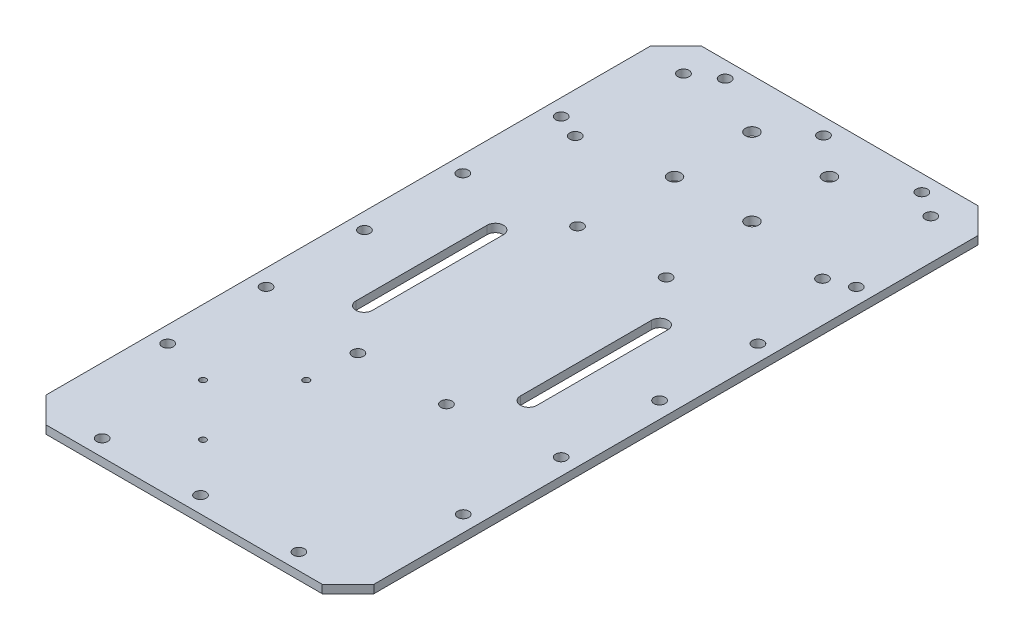
SolidWorks part; units mm, degrees
ref_plane "Front Plane" through (0, 0, 0) normal (0, 0, 1) x (1, 0, 0)
ref_plane "Top Plane" through (0, 0, 0) normal (0, 1, 0) x (1, 0, 0)
ref_plane "Right Plane" through (0, 0, 0) normal (1, 0, 0) x (0, 0, -1)
sketch "Sketch2" plane through (0, 0, 0) normal (0, 1, 0) x (1, 0, 0)
  line L0 (0, 10) -> (0, 244)
  line L1 (10, 254) -> (117, 254)
  line L2 (127, 244) -> (127, 10)
  line L3 (117, 0) -> (10, 0)
  line L4 (0, 244) -> (10, 254)
  line L5 (117, 254) -> (127, 244)
  line L6 (127, 10) -> (117, 0)
  line L7 (10, 0) -> (0, 10)
  line L8 (63.5, 254) -> (63.5, 243.84) construction
  line L9 (15.621, 241.3) -> (15.621, 199.39) construction
  line L10 (0, 127) -> (127, 127) construction
  line L11 (63.5, 243.84) -> (63.5, 199.39) construction
  line L12 (15.621, 199.39) -> (111.379, 199.39) construction
  line L13 (111.379, 199.39) -> (111.379, 241.3) construction
  line L14 (111.379, 241.3) -> (15.621, 241.3) construction
  line L15 (63.5, 127) -> (46.355, 127) construction
  line L16 (46.355, 127) -> (46.355, 169.545) construction
  line L17 (46.355, 169.545) -> (80.645, 169.545) construction
  line L18 (80.645, 169.545) -> (80.645, 84.455) construction
  line L19 (80.645, 84.455) -> (46.355, 84.455) construction
  line L20 (46.355, 84.455) -> (46.355, 127) construction
  line L21 (63.5, 127) -> (92.202, 127)
  line L27 (34.8088, 101.6) -> (34.8088, 114.3)
  line L29 (28.4588, 139.7) -> (28.4588, 101.6)
  line L31 (34.8088, 114.3) -> (34.8088, 139.7)
  line L34 (48.5, 205.9228) -> (48.5, 234.95) construction
  line L35 (48.5, 234.95) -> (78.5, 234.95) construction
  line L36 (78.5, 234.95) -> (78.5, 204.9501) construction
  line L37 (78.5, 204.9501) -> (48.5, 204.9501) construction
  line L38 (48.5, 204.9501) -> (48.5, 205.9228) construction
  line L43 (31.6338, 152.4) -> (31.6338, 101.6) construction
  line L44 (34.8088, 152.4) -> (34.8088, 101.6)
  line L45 (28.4588, 152.4) -> (28.4588, 101.6)
  line L46 (63.5, 0) -> (63.5, 254) construction
  line L47 (95.3662, 152.4) -> (95.3662, 101.6) construction
  line L48 (92.1912, 152.4) -> (92.1912, 101.6)
  line L49 (98.5412, 152.4) -> (98.5412, 101.6)
  circle A0 centre (6.35, 88.9) radius 2.159
  circle A1 centre (6.35, 165.1) radius 2.159
  circle A2 centre (120.65, 165.1) radius 2.159
  circle A3 centre (120.81, 50.8) radius 2.159
  circle A4 centre (6.35, 50.8) radius 2.159
  circle A13 centre (25.4, 247.65) radius 2.159
  circle A14 centre (101.6, 247.65) radius 2.159
  circle A15 centre (101.6, 6.35) radius 2.159
  circle A16 centre (25.4, 6.35) radius 2.159
  circle A17 centre (15.621, 241.3) radius 2.159
  circle A18 centre (15.621, 199.39) radius 2.159
  circle A19 centre (111.379, 199.39) radius 2.159
  circle A20 centre (111.379, 241.3) radius 2.159
  circle A22 centre (46.355, 169.545) radius 2.159
  circle A23 centre (46.355, 84.455) radius 2.159
  circle A24 centre (80.645, 84.455) radius 2.159
  circle A25 centre (80.645, 169.545) radius 2.159
  circle A26 centre (120.65, 88.9) radius 2.159
  circle A27 centre (48.5, 234.95) radius 2.54
  circle A30 centre (78.5, 234.95) radius 2.54
  circle A31 centre (78.5, 204.9501) radius 2.54
  circle A34 centre (48.5, 204.9501) radius 2.54
  circle A36 centre (120.65, 203.2) radius 2.159
  arc A38 (34.8088, 152.4) -> (28.4588, 152.4) centre (31.6338, 152.4) ccw
  arc A39 (28.4588, 101.6) -> (34.8088, 101.6) centre (31.6338, 101.6) ccw
  arc A40 (92.1912, 152.4) -> (98.5412, 152.4) centre (95.3662, 152.4) cw
  arc A41 (98.5412, 101.6) -> (92.1912, 101.6) centre (95.3662, 101.6) cw
  circle A42 centre (6.35, 203.2) radius 2.159
  circle A43 centre (63.5, 247.65) radius 2.159
  circle A44 centre (63.5, 6.35) radius 2.159
  circle A45 centre (120.65, 127) radius 2.159
  circle A46 centre (6.35, 127) radius 2.159
  circle A47 centre (25.4, 45.4) radius 1.25
  circle A48 centre (45.4, 65.4) radius 1.25
  circle A49 centre (45.4, 25.4) radius 1.25
  point P0 (0, 0)
  point P1 (0, 254)
  point P3 (127, 254)
  point P4 (127, 0)
  point P32 (31.6338, 127)
  point P73 (95.3662, 127)
  point P99 (0, 0)
  dimension "D1" = 12.7
  dimension "D2" = 254
  dimension "D8" = 6.35
  dimension "D9" = 6.35
  dimension "D10" = 38.1
  dimension "D11" = 38.1
  dimension "D13" = 38.1
  dimension "D14" = 38.1
  dimension "D16" = 6.35
  dimension "D17" = 6.35
  dimension "D18" = 6.35
  dimension "D20" = 38.1
  dimension "D21" = 6.35
  dimension "D22" = 6.35
  dimension "D23" = 6.35
  dimension "D24" = 38.1
  dimension "D25" = 29.9999
  dimension "D26" = 29.9999
  dimension "D27" = 5.08
  dimension "D28" = 5.08
  dimension "D29" = 5.08
  dimension "D30" = 38.1
  dimension "D31" = 6.35
  dimension "D32" = 4.318
  dimension "D33" = 4.318
  dimension "D34" = 4.318
  dimension "D35" = 4.318
  dimension "D36" = 4.318
  dimension "D37" = 4.318
  dimension "D38" = 4.318
  dimension "D39" = 4.318
  dimension "D40" = 20
  dimension "D41" = 40
  dimension "D42" = 20
  dimension "D43" = 2.5
  dimension "D44" = 4.318
  dimension "D45" = 6.35
  dimension "D46" = 4.318
  dimension "D47" = 6.35
  dimension "D48" = 4.318
  dimension "D49" = 6.35
  dimension "D50" = 4.318
  dimension "D51" = 6.35
  dimension "D55" = 4.318
  dimension "D56" = 4.318
  dimension "D57" = 2.5
  dimension "D58" = 4.318
  dimension "D59" = 2.5
  dimension "D60" = 25.4
  dimension "D7" = 127
  dimension "D12" = 38.1
  dimension "D15" = 38.1
  dimension "D19" = 25.4
  dimension "D52" = 19.05
  dimension "D53" = 34.29
  dimension "D54" = 85.09
  dimension "D61" = 25.4
extrude "Boss-Extrude1" add sketch "Sketch2" along normal blind 3.175 contours L7 L3 L6 L2 L5 L1 L4 L0 A46 A45 A44 A43 A42 A39 L29 L45 A38 L44 L31 L27 A34 A31 A26 A23 A22 A19 A18 A17 A14 A13 A4 A0
